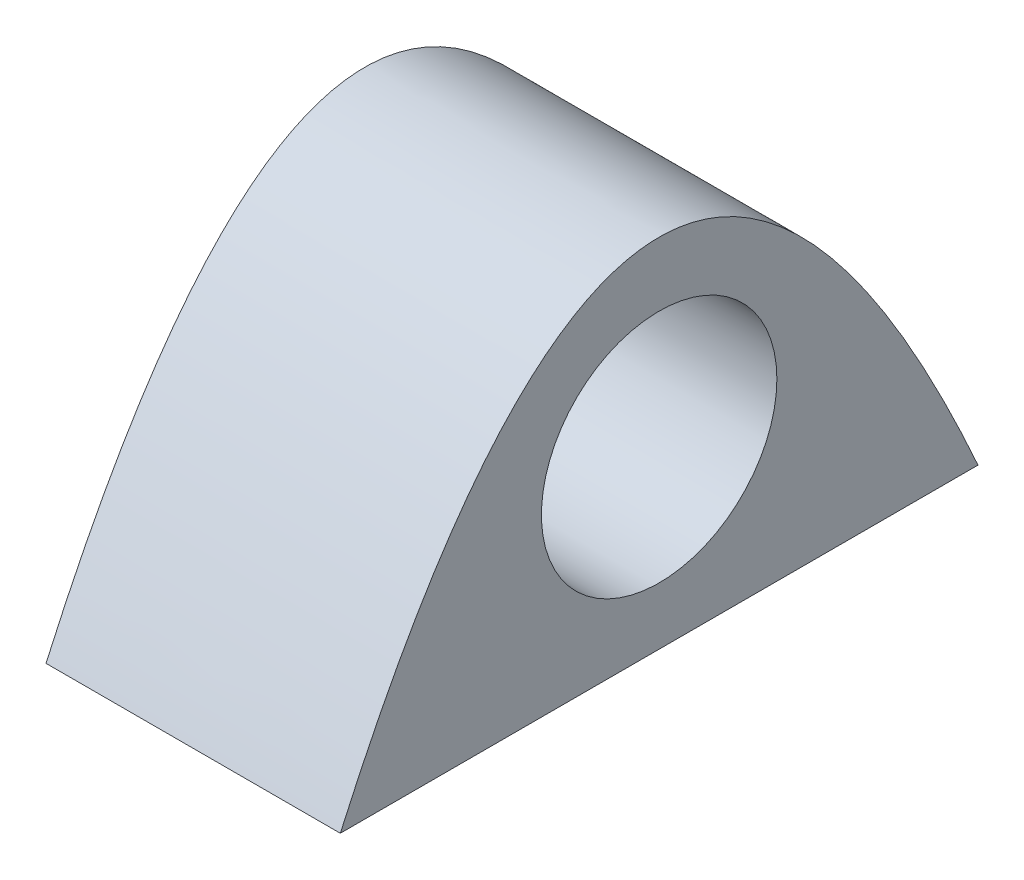
SolidWorks part; units mm, degrees
ref_plane "前视基准面" through (0, 0, 0) normal (0, 0, 1) x (1, 0, 0)
ref_plane "上视基准面" through (0, 0, 0) normal (0, 1, 0) x (1, 0, 0)
ref_plane "右视基准面" through (0, 0, 0) normal (1, 0, 0) x (0, 0, -1)
other "Configuration Table"
sketch "草图1" plane through (0, 0, 0) normal (1, 0, 0) x (0, 0, -1)
  line L0 (-3.25, 0) -> (3.25, 0)
  spline S0 degree 2 poles (-3.25, 0) (0, 7.2754) (3.25, 0) knots 0 0 0 1 1 1
  point P4 (0, 0)
extrude "凸台-拉伸1" add sketch "草图1" along normal blind 3 contours S0 L0
sketch "草图2" plane through (3, 0, 0) normal (1, 0, 0) x (0, 0, -1)
  circle A0 centre (0, 1.7849) radius 1.2
extrude "切除-拉伸1" cut sketch "草图2" against normal through all
